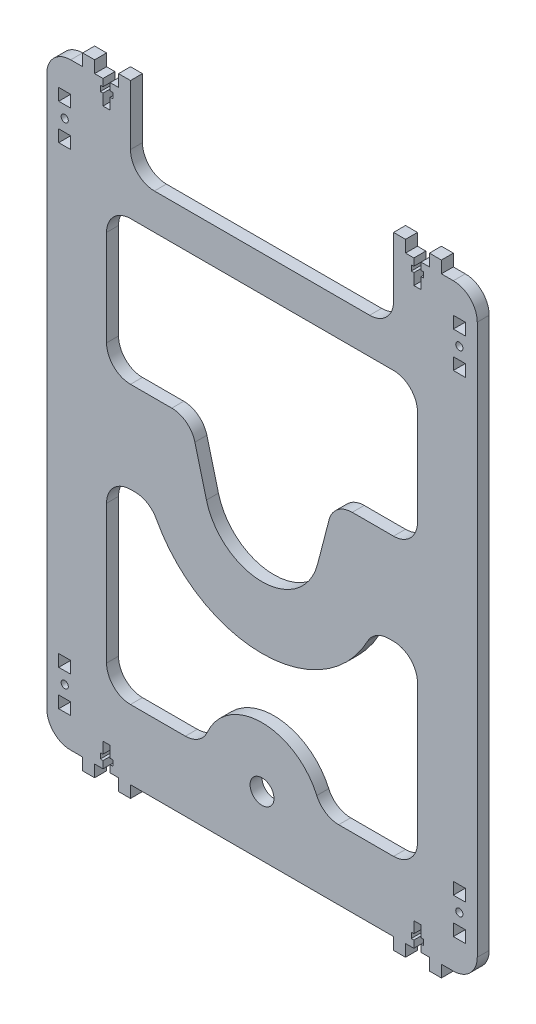
SolidWorks part; units mm, degrees
ref_plane "Front Plane" through (0, 0, 0) normal (0, 0, 1) x (1, 0, 0)
ref_plane "Top Plane" through (0, 0, 0) normal (0, 1, 0) x (1, 0, 0)
ref_plane "Right Plane" through (0, 0, 0) normal (1, 0, 0) x (0, 0, -1)
sketch "Sketch1" plane through (0, 0, 0) normal (0, 0, 1) x (1, 0, 0)
  line L0 (0, 0) -> (187.0096, 0) construction
  line L1 (-90, 125) -> (-55, 125) construction
  line L2 (-90, 125) -> (-90, -125)
  line L3 (-90, -125) -> (90, -125)
  line L4 (90, 125) -> (90, -125)
  line L5 (0, 0) -> (0, 134.5508) construction
  line L6 (-23.2273, -6.0409) -> (-30, 20)
  line L7 (-65, 80) -> (65, 80)
  line L8 (65, 80) -> (65, 0) construction
  line L9 (65, 0) -> (-65, 0) construction
  line L10 (-65, 0) -> (-65, 80) construction
  line L11 (-65, 0) -> (-20, 0) construction
  line L12 (20, 0) -> (65, 0) construction
  line L13 (82.5, 125) -> (82.5, -125) construction
  line L14 (0, 0) -> (0, -125) construction
  line L21 (-30, 20) -> (-65, 20)
  line L22 (-65, 20) -> (-65, 80)
  line L23 (65, 20) -> (65, 80)
  line L24 (30, 20) -> (65, 20)
  line L26 (-90, 125) -> (-55, 125)
  line L27 (23.2273, -6.0409) -> (30, 20)
  line L28 (-55, 125) -> (-55, 95)
  line L29 (-55, 95) -> (55, 95)
  line L30 (55, 95) -> (55, 125)
  line L31 (55, 125) -> (90, 125) construction
  line L32 (55, 125) -> (90, 125)
  line L33 (-46.616, -18.0816) -> (-65, -18.0816)
  line L34 (-65, -18.0816) -> (-65, -95.958)
  line L35 (-65, -95.958) -> (-24.6711, -95.958)
  line L36 (46.616, -18.0816) -> (65, -18.0816)
  line L37 (65, -18.0816) -> (65, -95.958)
  line L38 (65, -95.958) -> (24.6711, -95.958)
  circle A1 centre (0, -100) radius 5
  circle A2 centre (0, 0) radius 24 construction
  arc A3 (23.2273, -6.0409) -> (-23.2273, -6.0409) centre (0, 0) cw
  circle A4 centre (0, 0) radius 50 construction
  circle A5 centre (0, -100) radius 25 construction
  arc A6 (24.6711, -95.958) -> (-24.6711, -95.958) centre (0, -100) ccw
  arc A7 (-46.616, -18.0816) -> (46.616, -18.0816) centre (0, 0) ccw
  line B0 (82.5, 107.5) -> (82.5, 97.5) construction
  line B1 (80, 107.5) -> (80, 112.5)
  line B2 (80, 107.5) -> (85, 107.5)
  line B3 (85, 107.5) -> (85, 112.5)
  line B4 (80, 112.5) -> (85, 112.5)
  line B5 (80, 97.5) -> (80, 92.5)
  line B6 (80, 97.5) -> (85, 97.5)
  line B7 (85, 97.5) -> (85, 92.5)
  line B8 (80, 92.5) -> (85, 92.5)
  line B9 (82.5, 102.5) -> (75.5276, 102.5) construction
  circle B10 centre (82.5, 102.5) radius 1.5
  line B11 (82.5, -107.5) -> (82.5, -97.5) construction
  line B12 (80, -107.5) -> (80, -112.5)
  line B13 (80, -107.5) -> (85, -107.5)
  line B14 (85, -107.5) -> (85, -112.5)
  line B15 (80, -112.5) -> (85, -112.5)
  line B16 (80, -97.5) -> (80, -92.5)
  line B17 (80, -97.5) -> (85, -97.5)
  line B18 (85, -97.5) -> (85, -92.5)
  line B19 (80, -92.5) -> (85, -92.5)
  line B20 (82.5, -102.5) -> (75.5276, -102.5) construction
  circle B21 centre (82.5, -102.5) radius 1.5
  line B22 (-82.5, 107.5) -> (-82.5, 97.5) construction
  line B23 (-80, 107.5) -> (-80, 112.5)
  line B24 (-80, 107.5) -> (-85, 107.5)
  line B25 (-85, 107.5) -> (-85, 112.5)
  line B26 (-80, 112.5) -> (-85, 112.5)
  line B27 (-80, 97.5) -> (-80, 92.5)
  line B28 (-80, 97.5) -> (-85, 97.5)
  line B29 (-85, 97.5) -> (-85, 92.5)
  line B30 (-80, 92.5) -> (-85, 92.5)
  line B31 (-82.5, 102.5) -> (-75.5276, 102.5) construction
  circle B32 centre (-82.5, 102.5) radius 1.5
  line B33 (-82.5, -107.5) -> (-82.5, -97.5) construction
  line B34 (-80, -107.5) -> (-80, -112.5)
  line B35 (-80, -107.5) -> (-85, -107.5)
  line B36 (-85, -107.5) -> (-85, -112.5)
  line B37 (-80, -112.5) -> (-85, -112.5)
  line B38 (-80, -97.5) -> (-80, -92.5)
  line B39 (-80, -97.5) -> (-85, -97.5)
  line B40 (-85, -97.5) -> (-85, -92.5)
  line B41 (-80, -92.5) -> (-85, -92.5)
  line B42 (-82.5, -102.5) -> (-75.5276, -102.5) construction
  circle B43 centre (-82.5, -102.5) radius 1.5
  line B44 (-67.6, -122) -> (-67.6, -119.7)
  line B45 (-63.5, -119.7) -> (-63.5, -115)
  line B46 (-66.5, -115) -> (-66.5, -119.7)
  line B47 (-67.6, -119.7) -> (-66.5, -119.7)
  line B48 (-65, -125) -> (-65, -113.7792) construction
  line B49 (-66.5, -125) -> (-70, -125)
  line B50 (-70, -130) -> (-75, -130)
  line B51 (-75, -130) -> (-75, -125)
  line B52 (-70, -130) -> (-70, -125)
  line B53 (-63.5, -125) -> (-60, -125)
  line B54 (-60, -125) -> (-60, -130)
  line B55 (-60, -130) -> (-55, -130)
  line B56 (-55, -130) -> (-55, -125)
  line B57 (-66.5, -125) -> (-63.5, -125) construction
  line B58 (-63.5, -125) -> (-63.5, -122)
  line B59 (-63.5, -119.7) -> (-62.4, -119.7)
  line B60 (-62.4, -122) -> (-63.5, -122)
  line B61 (-63.5, -115) -> (-66.5, -115)
  line B62 (-66.5, -122) -> (-67.6, -122)
  line B63 (-62.4, -119.7) -> (-62.4, -122)
  line B64 (-66.5, -122) -> (-66.5, -125)
  line B65 (-65, -115) -> (-65, -125) construction
  line B66 (62.4, -122) -> (62.4, -119.7)
  line B67 (66.5, -119.7) -> (66.5, -115)
  line B68 (63.5, -115) -> (63.5, -119.7)
  line B69 (62.4, -119.7) -> (63.5, -119.7)
  line B70 (65, -125) -> (65, -113.7792) construction
  line B71 (63.5, -125) -> (60, -125)
  line B72 (60, -130) -> (55, -130)
  line B73 (55, -130) -> (55, -125)
  line B74 (60, -130) -> (60, -125)
  line B75 (66.5, -125) -> (70, -125)
  line B76 (70, -125) -> (70, -130)
  line B77 (70, -130) -> (75, -130)
  line B78 (75, -130) -> (75, -125)
  line B79 (63.5, -125) -> (66.5, -125) construction
  line B80 (66.5, -125) -> (66.5, -122)
  line B81 (66.5, -119.7) -> (67.6, -119.7)
  line B82 (67.6, -122) -> (66.5, -122)
  line B83 (66.5, -115) -> (63.5, -115)
  line B84 (63.5, -122) -> (62.4, -122)
  line B85 (67.6, -119.7) -> (67.6, -122)
  line B86 (63.5, -122) -> (63.5, -125)
  line B87 (65, -115) -> (65, -125) construction
  line B88 (67.6, 122) -> (67.6, 119.7)
  line B89 (63.5, 119.7) -> (63.5, 115)
  line B90 (66.5, 115) -> (66.5, 119.7)
  line B91 (67.6, 119.7) -> (66.5, 119.7)
  line B92 (65, 125) -> (65, 113.7792) construction
  line B93 (66.5, 125) -> (70, 125)
  line B94 (70, 130) -> (75, 130)
  line B95 (75, 130) -> (75, 125)
  line B96 (70, 130) -> (70, 125)
  line B97 (63.5, 125) -> (60, 125)
  line B98 (60, 125) -> (60, 130)
  line B99 (60, 130) -> (55, 130)
  line B100 (55, 130) -> (55, 125)
  line B101 (66.5, 125) -> (63.5, 125) construction
  line B102 (63.5, 125) -> (63.5, 122)
  line B103 (63.5, 119.7) -> (62.4, 119.7)
  line B104 (62.4, 122) -> (63.5, 122)
  line B105 (63.5, 115) -> (66.5, 115)
  line B106 (66.5, 122) -> (67.6, 122)
  line B107 (62.4, 119.7) -> (62.4, 122)
  line B108 (66.5, 122) -> (66.5, 125)
  line B109 (65, 115) -> (65, 125) construction
  line B110 (-62.4, 122) -> (-62.4, 119.7)
  line B111 (-66.5, 119.7) -> (-66.5, 115)
  line B112 (-63.5, 115) -> (-63.5, 119.7)
  line B113 (-62.4, 119.7) -> (-63.5, 119.7)
  line B114 (-65, 125) -> (-65, 113.7792) construction
  line B115 (-63.5, 125) -> (-60, 125)
  line B116 (-60, 130) -> (-55, 130)
  line B117 (-55, 130) -> (-55, 125)
  line B118 (-60, 130) -> (-60, 125)
  line B119 (-66.5, 125) -> (-70, 125)
  line B120 (-70, 125) -> (-70, 130)
  line B121 (-70, 130) -> (-75, 130)
  line B122 (-75, 130) -> (-75, 125)
  line B123 (-63.5, 125) -> (-66.5, 125) construction
  line B124 (-66.5, 125) -> (-66.5, 122)
  line B125 (-66.5, 119.7) -> (-67.6, 119.7)
  line B126 (-67.6, 122) -> (-66.5, 122)
  line B127 (-66.5, 115) -> (-63.5, 115)
  line B128 (-63.5, 122) -> (-62.4, 122)
  line B129 (-67.6, 119.7) -> (-67.6, 122)
  line B130 (-63.5, 122) -> (-63.5, 125)
  line B131 (-65, 115) -> (-65, 125) construction
  dimension "D8" = 50
  dimension "D10" = 10
  dimension "D2" = 24
  dimension "D13" = 100
  dimension "D3" = 250
  dimension "D4" = 180
  dimension "D5" = 35
  dimension "D6" = 25
  dimension "D7" = 20
  dimension "D9" = 22.5
  dimension "D11" = 25
  dimension "D12" = 7.5
  dimension "D14" = 15
  dimension "D15" = 30
sketch_block_instance "Trou M3 plots 5mm-7"
sketch_block "Trou M3 plots 5mm" parameters "D2"=3, "D1"=5, "D3"=5, "D4"=10
sketch_block_instance "Trou M3 plots 5mm-8"
sketch_block_instance "Trou M3 plots 5mm-9"
sketch_block_instance "Trou M3 plots 5mm-10"
sketch_block_instance "Insert M3 plots ep 5mm-1"
sketch_block "Insert M3 plots ep 5mm" parameters "D1"=10, "D2"=5, "D3"=5
sketch_block_instance "Decoupe Insert M3-4"
sketch_block "Decoupe Insert M3" parameters "D1"=5.2, "D2"=3, "D3"=2.3, "D4"=3, "D5"=10
sketch_block_instance "Insert M3 plots ep 5mm-2"
sketch_block_instance "Insert M3 plots ep 5mm-3"
sketch_block_instance "Insert M3 plots ep 5mm-5"
extrude "Boss-Extrude1" add sketch "Sketch1" along normal blind 5 contours B130 B128 B110 B113 B112 B127 B111 B125 B129 B126 B124 L26 L2 L3 B64 B62 B44 B47 B46 B61 B45 B59 B63 B60 B58 B86 B84 B66 B69 B68 B83 B67 B81 B85 B82 B80 L4 | B50 B52 L3 B51 | B55 B56 L3 B54 | B72 B74 L3 B73 | B77 B78 L3 B76 | B121 B122 L26 B120 | B116 B118 L26 B117 | B99 B100 L26 B98 | B94 B96 L26 B95
fillet "Fillet1" radius 10 20 edges at (-65, -18.0816, 2.5) (-65, -95.958, 2.5) (-24.6711, -95.958, 2.5) (24.6711, -95.958, 2.5) (65, -95.958, 2.5) (65, -18.0816, 2.5) (46.616, -18.0816, 2.5) (-46.616, -18.0816, 2.5) (30, 20, 2.5) (65, 20, 2.5) (65, 80, 2.5) (-65, 80, 2.5) (-65, 20, 2.5) (-30, 20, 2.5) (-55, 95, 2.5) (55, 95, 2.5) (90, 125, 2.5) (90, -125, 2.5) (-90, -125, 2.5) (-90, 125, 2.5)
